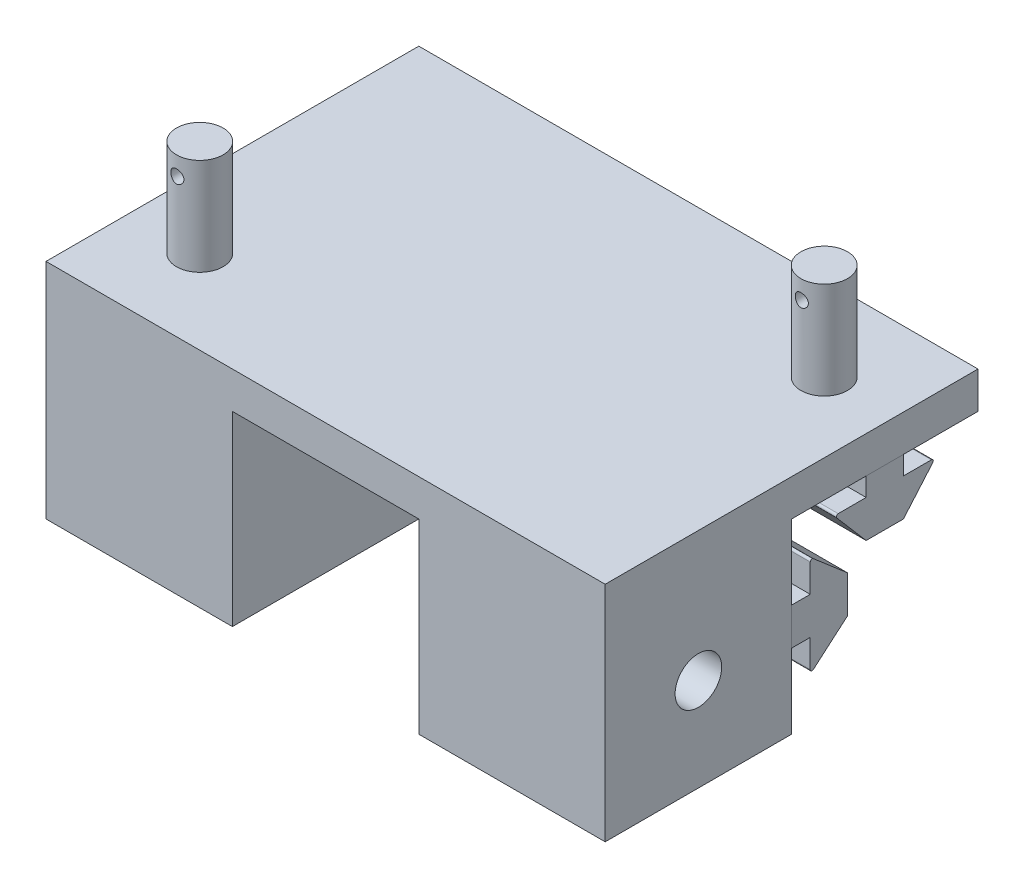
SolidWorks part; units mm, degrees
ref_plane "Front Plane" through (0, 0, 0) normal (0, 0, 1) x (1, 0, 0)
ref_plane "Top Plane" through (0, 0, 0) normal (0, 1, 0) x (1, 0, 0)
ref_plane "Right Plane" through (0, 0, 0) normal (1, 0, 0) x (0, 0, -1)
sketch "Sketch1" plane through (0, 0, 0) normal (0, 1, 0) x (1, 0, 0)
  line L1 (38.1, -25.4) -> (-38.1, -25.4)
  line L2 (38.1, -25.4) -> (38.1, 25.4)
  line L3 (38.1, 25.4) -> (-38.1, 25.4)
  line L4 (-38.1, -25.4) -> (-38.1, 25.4)
  line L5 (38.1, -25.4) -> (-38.1, 25.4) construction
  line L6 (38.1, 25.4) -> (-38.1, -25.4) construction
  point P0 (0, 0)
  dimension "D1" = 76.2
  dimension "D2" = 50.8
extrude "Boss-Extrude1" add sketch "Sketch1" along normal blind 5
sketch "Sketch6" plane through (0, 0, 0) normal (0, -1, 0) x (1, 0, 0)
  line L0 (-38.1, 0) -> (38.1, 0) construction
  line L1 (-38.1, -25.4) -> (-38.1, 25.4) construction
  line L2 (38.1, 25.4) -> (38.1, -25.4) construction
  line L4 (-38.1, 25.4) -> (-12.7, 25.4)
  line L5 (-38.1, 25.4) -> (-38.1, 0)
  line L6 (-38.1, 0) -> (-12.7, 0)
  line L7 (-12.7, 25.4) -> (-12.7, 0)
  line L8 (38.1, 25.4) -> (12.7, 25.4)
  line L9 (38.1, 25.4) -> (38.1, 0)
  line L10 (38.1, 0) -> (12.7, 0)
  line L11 (12.7, 25.4) -> (12.7, 0)
  dimension "D1" = 25.4
extrude "Boss-Extrude2" add sketch "Sketch6" along normal blind 25.4
hole_wizard "1/4 (0.25) Diameter Hole1" positions "Sketch7" profile "Sketch8" hole size "1/4" standard "ANSI Inch"
sketch "Sketch7" plane through (38.1, 0, 0) normal (1, 0, 0) x (0, 0, -1)
  point P0 (-12.7, -12.7)
sketch "Sketch8" plane through (38.1, -12.7, 12.7) normal (0, 1, 0) x (0, 0, -1)
  line L0 (0, 0) -> (0, 27.3067)
  line L1 (0, 27.3067) -> (3.175, 25.399)
  line L2 (3.175, 25.399) -> (3.175, 0)
  line L5 (3.175, 0) -> (0, 0)
  line L10 (0, 27.3067) -> (-3.175, 25.399) construction
  line L11 (0, -6.35) -> (0, 107.95) construction
  dimension "Hole Dia." = 6.35
  dimension "Hole Depth" = 25.399
  dimension "Drill Angle" = 118
sketch "Sketch10" plane through (38.1, 0, 0) normal (1, 0, 0) x (0, 0, -1)
  line L0 (0, -12.7) -> (12.7, -12.7) construction
  line L1 (0, -25.4) -> (0, 0) construction
  line L2 (12.7, -12.7) -> (12.7, 0) construction
  line L3 (0, 0) -> (25.4, 0) construction
  line L4 (19.05, -2.54) -> (6.35, -2.54)
  line L5 (6.1573, -2.9595) -> (10.16, -7.62)
  line L6 (19.2427, -2.9595) -> (15.24, -7.62)
  line L7 (15.24, -7.62) -> (10.16, -7.62)
  line L8 (7.62, -15.24) -> (7.62, -10.16)
  line L9 (7.62, -10.16) -> (2.9595, -6.1573)
  line L10 (2.54, -19.05) -> (2.54, -6.35)
  line L11 (2.9595, -19.2427) -> (7.62, -15.24)
  line L12 (0, -15.24) -> (0, -10.16)
  line L13 (0, -10.16) -> (2.54, -10.16)
  line L14 (2.54, -10.16) -> (2.54, -15.24)
  line L15 (2.54, -15.24) -> (0, -15.24)
  line L16 (15.24, 0) -> (10.16, 0)
  line L17 (10.16, 0) -> (10.16, -2.54)
  line L18 (10.16, -2.54) -> (15.24, -2.54)
  line L19 (15.24, -2.54) -> (15.24, 0)
  arc A0 (2.54, -19.05) -> (2.9595, -19.2427) centre (2.794, -19.05) ccw
  arc A1 (2.9595, -6.1573) -> (2.54, -6.35) centre (2.794, -6.35) ccw
  arc A2 (19.05, -2.54) -> (19.2427, -2.9595) centre (19.05, -2.794) cw
  arc A3 (6.35, -2.54) -> (6.1573, -2.9595) centre (6.35, -2.794) ccw
  point P4 (12.7, -7.62)
  point P10 (12.7, -2.54)
  point P17 (7.62, -12.7)
  point P20 (2.54, -12.7)
  point P30 (0, -12.7)
  point P35 (12.7, 0)
  line M15 (0, -25.4) -> (0, 0)
  line M16 (0, 0) -> (25.4, 0)
  dimension "D1" = 0.254
  dimension "D2" = 5.08
  dimension "D3" = 5.08
  dimension "D4" = 2.54
  dimension "D5" = 2.54
  dimension "D6" = 5.08
  dimension "D7" = 12.7
  dimension "D8" = 5.08
extrude "Boss-Extrude3" add sketch "Sketch10" against normal up to surface (76.2 mm away) separate body contours L15 L10 L13 M15 | L9 A1 L10 A0 L11 L8 | L4 A3 L5 L7 L6 A2 | L4 L19 L17 M16 up to face at (-38.1, -6.8, 0)
sketch "Sketch11" plane through (0, 0, 25.4) normal (0, 0, 1) x (1, 0, 0)
  line L1 (-12.7, 0) -> (12.7, 0)
  line L2 (-12.7, 0) -> (-12.7, -25.4)
  line L3 (-12.7, -25.4) -> (12.7, -25.4)
  line L4 (12.7, 0) -> (12.7, -25.4)
extrude "Cut-Extrude2" cut sketch "Sketch11" against normal up to surface (50.8 mm away) up to face at (0, 2.5, -25.4)
sketch "Sketch17" plane through (0, 5, 0) normal (0, 1, 0) x (1, 0, 0)
  circle A0 centre (-28.575, -13.97) radius 3.175
  circle A1 centre (28.575, 13.97) radius 3.175
  point P0 (28.575, 13.97)
  point P1 (-28.575, -13.97)
  dimension "D1" = 6.35
extrude "Boss-Extrude4" add sketch "Sketch17" along normal blind 13.208
sketch "Sketch18" plane through (0, 0, -25.4) normal (0, 0, -1) x (-1, 0, 0)
  line L0 (-28.575, 18.208) -> (-28.575, 0) construction
  line L1 (-25.4, 18.208) -> (-31.75, 18.208) construction
  line L2 (-38.1, 0) -> (38.1, 0) construction
  line L3 (28.575, 18.208) -> (28.575, 0) construction
  line L4 (31.75, 18.208) -> (25.4, 18.208) construction
  circle A0 centre (-28.575, 15.668) radius 0.889
  circle A1 centre (28.575, 15.668) radius 0.889
  dimension "D1" = 1.778
  dimension "D2" = 2.54
  dimension "D3" = 2.54
extrude "Cut-Extrude3" cut sketch "Sketch18" against normal through all
